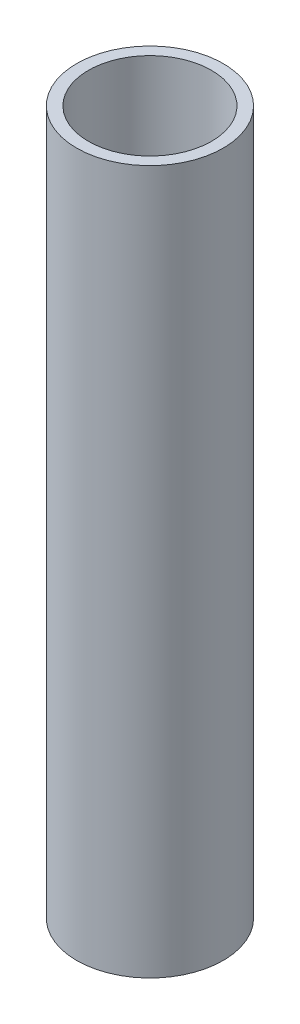
SolidWorks part; units mm, degrees
ref_plane "Front Plane" through (0, 0, 0) normal (0, 0, 1) x (1, 0, 0)
ref_plane "Top Plane" through (0, 0, 0) normal (0, 1, 0) x (1, 0, 0)
ref_plane "Right Plane" through (0, 0, 0) normal (1, 0, 0) x (0, 0, -1)
sketch "Sketch1" plane through (0, 0, 0) normal (0, 1, 0) x (1, 0, 0)
  circle A0 centre (0, 0) radius 12.5
  dimension "D1" = 25
extrude "Extrude-Thin1" add sketch "Sketch1" along normal blind 120 thin thin type one direction reverse wall 2
sketch "Sketch2" plane through (0, 0, 0) normal (0, -1, 0) x (1, 0, 0)
  line L0 (0, 19.1081) -> (0, -21.0572) construction
  line L2 (-13.226, 0) -> (13.8873, 0) construction
ref_plane "Plane1" through (0, 0, 0) normal (1, 0, 0) x (0, 0, -1)
ref_plane "Plane2" through (0, 0, 0) normal (0, 0, 1) x (1, 0, 0)
